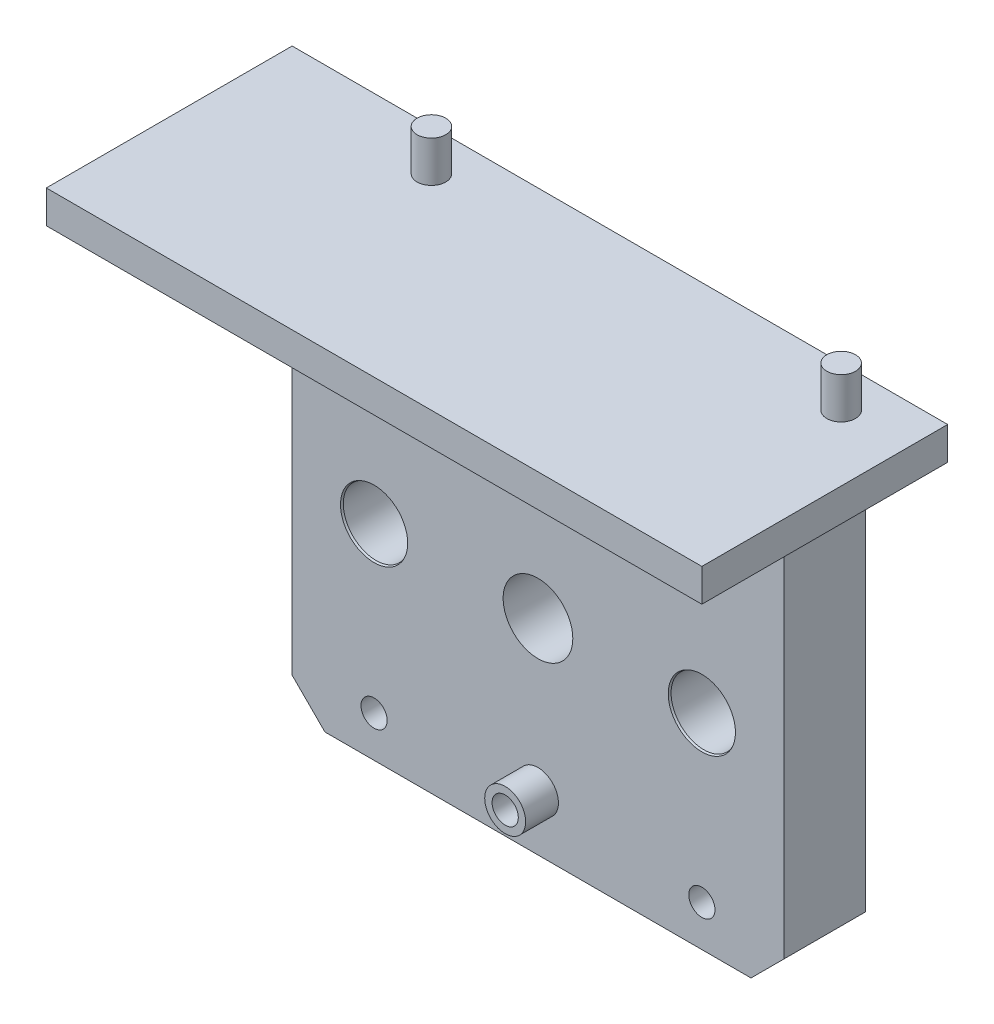
SolidWorks part; units mm, degrees
ref_plane "前视基准面" through (0, 0, 0) normal (0, 0, 1) x (1, 0, 0)
ref_plane "上视基准面" through (0, 0, 0) normal (0, 1, 0) x (1, 0, 0)
ref_plane "右视基准面" through (0, 0, 0) normal (1, 0, 0) x (0, 0, -1)
other "Configuration Table"
sketch "草图1" plane through (0, 0, 0) normal (0, 0, 1) x (1, 0, 0)
  line L1 (-30, -25) -> (30, -25)
  line L2 (-30, -25) -> (-30, 25)
  line L3 (-30, 25) -> (30, 25)
  line L4 (30, -25) -> (30, 25)
  line L5 (-30, -25) -> (30, 25) construction
  line L6 (-30, 25) -> (30, -25) construction
  point P0 (0, 0)
  dimension "D1" = 50
  dimension "D2" = 60
extrude "凸台-拉伸1" add sketch "草图1" along normal blind 10
hole_wizard "孔1" positions "草图2" profile "草图3" legacy
sketch "草图2" plane through (0, 0, 10) normal (0, 0, 1) x (1, 0, 0)
  point P0 (0, 0)
sketch "草图3" plane through (0, 0, 10) normal (1, 0, 0) x (0, -1, 0)
  line L0 (0, 0) -> (0, 20)
  line L1 (0, 20) -> (4.25, 20)
  line L2 (4.25, 20) -> (4.25, 0)
  line L3 (4.25, 0) -> (0, 0)
  line L4 (0, 110) -> (0, -10) construction
  dimension "直径" = 8.5
  dimension "深度" = 20
hole_wizard "孔2" positions "草图4" profile "草图5" legacy end condition through all
sketch "草图4" plane through (0, 0, 10) normal (0, 0, 1) x (1, 0, 0)
  point P0 (20, 0)
  point P2 (-20, 0)
  dimension "D1" = 20
  dimension "D2" = 20
sketch "草图5" plane through (20, 0, 10) normal (1, 0, 0) x (0, -1, 0)
  line L0 (0, 0) -> (0, 10)
  line L1 (0, 10) -> (4, 10)
  line L2 (4, 10) -> (4, 0.2414)
  line L3 (4, 0.2414) -> (4.1, 0)
  line L4 (4.1, 0) -> (0, 0)
  line L5 (0, -6.4453) -> (0, 115.525) construction
  line L6 (-4, 0.2414) -> (-4.1, 0) construction
  dimension "直径" = 8
  dimension "深度" = 10
  dimension "锥坑角度" = 45
  dimension "锥坑直径" = 8.2
sketch "草图9" plane through (0, 0, 10) normal (0, 0, 1) x (1, 0, 0)
  circle A0 centre (0, 18.25) radius 2.5
  circle A1 centre (0, -18.25) radius 2.5
  dimension "D1" = 5
  dimension "D2" = 5
  dimension "D3" = 18.25
  dimension "D4" = 18.25
extrude "凸台-拉伸3" add sketch "草图9" along normal blind 4
hole_wizard "孔3" positions "草图10" profile "草图11" legacy end condition through all
sketch "草图10" plane through (0, 0, 14) normal (0, 0, 1) x (1, 0, 0)
  point P0 (0, 18.25)
  point P3 (0, -18.25)
sketch "草图11" plane through (0, 18.25, 14) normal (1, 0, 0) x (0, -1, 0)
  line L0 (0, 0) -> (0, 14)
  line L1 (0, 14) -> (1.6, 14)
  line L2 (1.6, 14) -> (1.6, 0)
  line L3 (1.6, 0) -> (0, 0)
  line L4 (0, 110) -> (0, -10) construction
  dimension "直径" = 3.2
  dimension "深度" = 14
sketch "草图15" plane through (0, 0, 10) normal (0, 0, 1) x (1, 0, 0)
  line L0 (-30, 0) -> (30, 0)
  line L1 (-30, 25) -> (-30, -25) construction
  line L2 (30, -25) -> (30, 25) construction
  line L3 (0, 25) -> (0, -25)
  line L4 (30, 25) -> (-30, 25) construction
  line L5 (-30, -25) -> (30, -25) construction
  line L6 (0, 0) -> (-29.5019, 29.5019)
  line L8 (30, 14.0027) -> (14.0027, 14.0027)
  line L9 (-30, 25) -> (-14.0027, 25)
  line L10 (-30, 25) -> (-30, 14.0027)
  line L11 (-30, 14.0027) -> (-14.0027, 14.0027)
  line L12 (-14.0027, 25) -> (-14.0027, 14.0027)
  line L13 (14.0027, 25) -> (14.0027, 14.0027)
  line L14 (30, 25) -> (14.0027, 25)
  line L15 (30, 25) -> (30, 14.0027)
  line L16 (-30, -14.0027) -> (-14.0027, -14.0027)
  line L17 (-14.0027, -25) -> (-14.0027, -14.0027)
  line L18 (-30, -25) -> (-14.0027, -25)
  line L19 (-30, -25) -> (-30, -14.0027)
  line L20 (30, -25) -> (30, -14.0027)
  line L21 (30, -25) -> (14.0027, -25)
  line L22 (14.0027, -25) -> (14.0027, -14.0027)
  line L23 (30, -14.0027) -> (14.0027, -14.0027)
  circle A0 centre (-20, 20) radius 1.6
  circle A1 centre (20, 20) radius 1.6
  circle A2 centre (20, -20) radius 1.6
  circle A3 centre (-20, -20) radius 1.6
  dimension "D3" = 3.2
  dimension "D1" = 45
  dimension "D2" = 40
chamfer "倒角1" distance 4 angle 45 2 edges at (30, -25, 5) (-30, -25, 5)
extrude "切除-拉伸1" cut sketch "草图15" against normal through all contours L6 A0 | L6 A0 | A1 | A2 | A3
sketch "草图16" plane through (0, 25, 0) normal (0, 1, 0) x (1, 0, 0)
  line L2 (30, -10) -> (-30, -10)
  line L3 (30, -10) -> (30, 0)
  line L4 (30, 0) -> (-30, 0)
  line L5 (-30, -10) -> (-30, 0)
extrude "凸台-拉伸4" add sketch "草图16" along normal blind 10.5
sketch "草图17" plane through (0, 35.5, 0) normal (0, 1, 0) x (1, 0, 0)
  line L1 (40, 0) -> (-40, 0)
  line L3 (40, 0) -> (40, -30)
  line L4 (40, -30) -> (-40, -30)
  line L5 (-40, 0) -> (-40, -30)
  line L6 (8, 0) -> (-40, -30) construction
  line L7 (40, -30) -> (-8, 0) construction
  point P0 (0, -5)
  dimension "D1" = 80
  dimension "D2" = 30
extrude "凸台-拉伸5" add sketch "草图17" against normal blind 4
sketch "草图18" plane through (0, 35.5, 0) normal (0, 1, 0) x (1, 0, 0)
  circle A0 centre (32, -5) radius 1.75
  circle A1 centre (-18, -5) radius 1.75
  dimension "D1" = 3.5
  dimension "D2" = 3.5
extrude "凸台-拉伸6" add sketch "草图18" along normal blind 5
